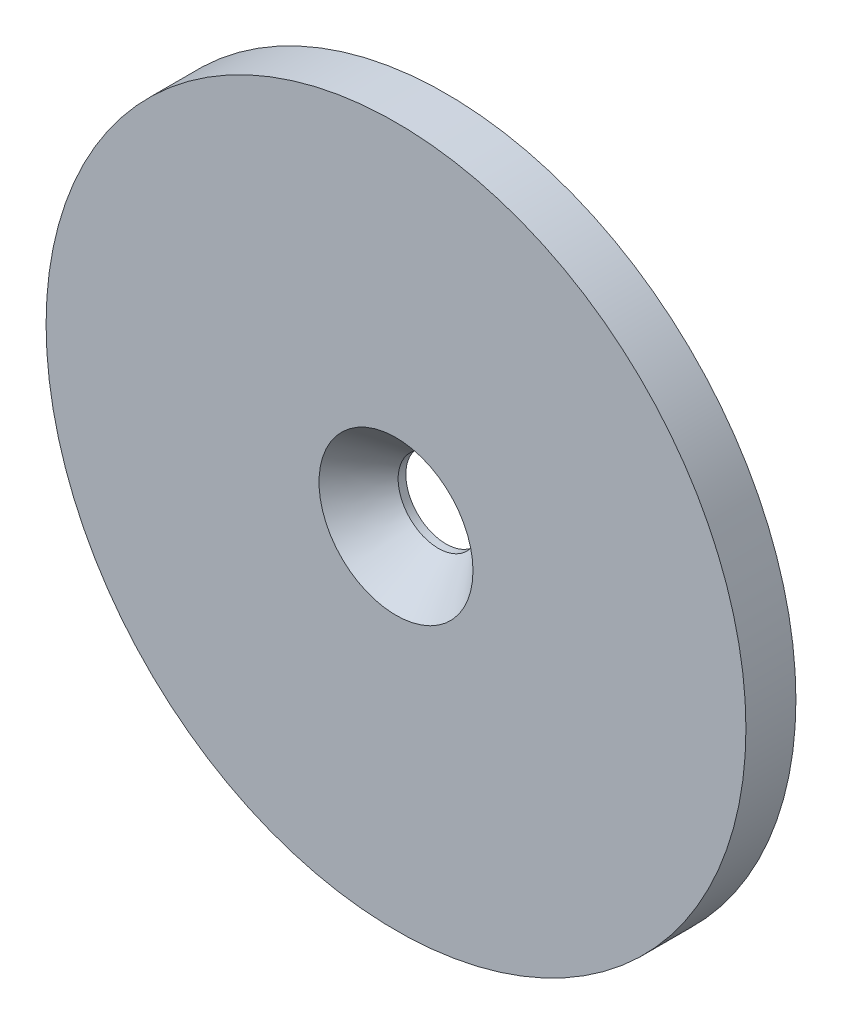
SolidWorks part; units mm, degrees
material "6061-T6 (SS)"
ref_plane "Front Plane" through (0, 0, 0) normal (0, 0, 1) x (1, 0, 0)
ref_plane "Top Plane" through (0, 0, 0) normal (0, 1, 0) x (1, 0, 0)
ref_plane "Right Plane" through (0, 0, 0) normal (1, 0, 0) x (0, 0, -1)
sketch "Sketch1" plane through (0, 0, 0) normal (0, 0, 1) x (1, 0, 0)
  circle A0 centre (0, 0) radius 22.225
  circle A1 centre (0, 0) radius 2.4892
  dimension "D1" = 44.45
  dimension "D2" = 4.9784
extrude "Boss-Extrude1" add sketch "Sketch1" along normal blind 3.175
hole_wizard "CSK for #10 Flat Head Machine Screw1" positions "3DSketch1" profile "Sketch2" countersink size "#10" standard "ANSI Inch" end condition through all
sketch3d "3DSketch1"
  line L0 (0, 0, 3.175) -> (0, 0, 0) construction
  point P0 (0, 0, 3.175)
sketch "Sketch2" plane through (0, 0, 3.175) normal (1, 0, 0) x (0, -1, 0)
  line L0 (0, 0) -> (0, 3.175)
  line L1 (0, 3.175) -> (2.5527, 3.175)
  line L2 (2.5527, 3.175) -> (2.5527, 2.6882)
  line L3 (2.5527, 2.6882) -> (4.8895, 0)
  line L5 (4.8895, 0) -> (0, 0)
  line L6 (-2.5527, 2.6882) -> (-4.8895, 0) construction
  line L11 (0, -6.35) -> (0, 107.95) construction
  dimension "Thru Hole Dia." = 5.1054
  dimension "Thru Hole Depth" = 3.175
  dimension "Near C'Sink Dia." = 9.779
  dimension "Near C'Sink Angle" = 82
